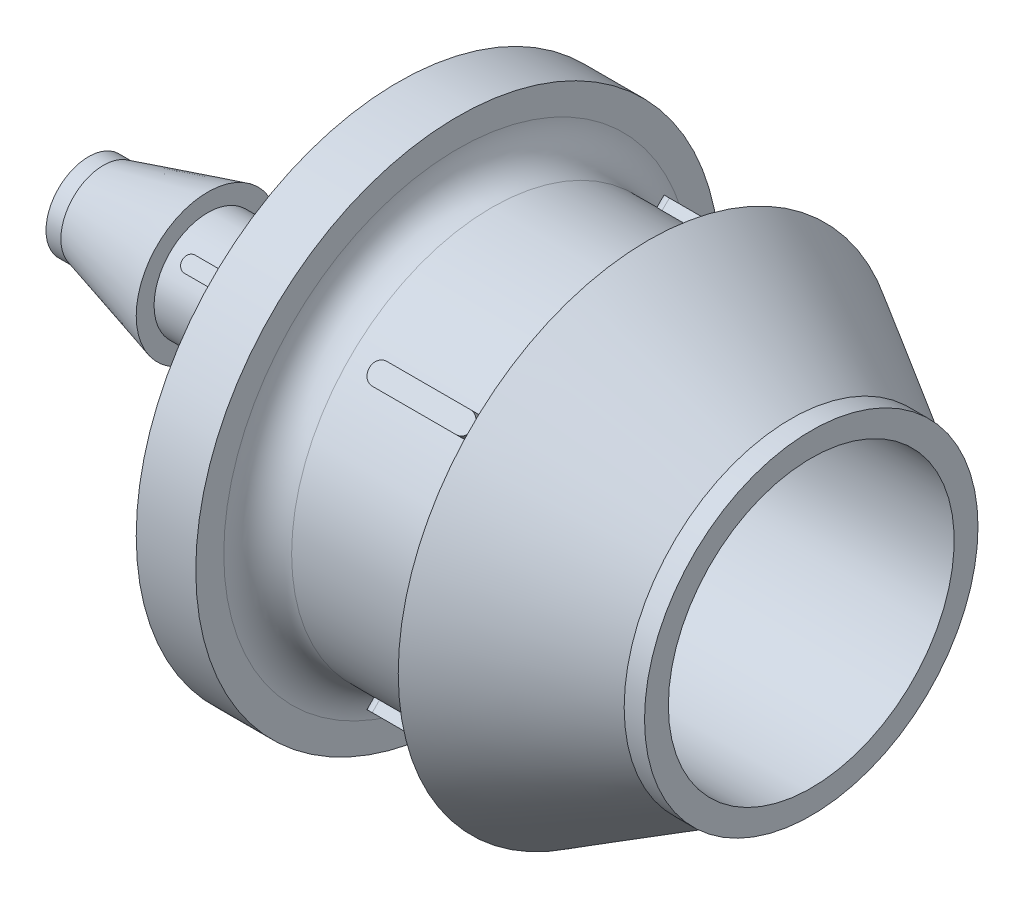
SolidWorks part; units mm, degrees
ref_plane "Front Plane" through (0, 0, 0) normal (0, 0, 1) x (1, 0, 0)
ref_plane "Top Plane" through (0, 0, 0) normal (0, 1, 0) x (1, 0, 0)
ref_plane "Right Plane" through (0, 0, 0) normal (1, 0, 0) x (0, 0, -1)
sketch "Sketch1" plane through (0, 0, 0) normal (0, 0, 1) x (1, 0, 0)
  line L0 (0, 0) -> (20.4343, 0) construction
  line L1 (20.4343, 7.62) -> (20.4343, 8.89)
  line L2 (-1.5875, 2.8575) -> (-1.5875, 13.97)
  line L3 (11.7475, 13.335) -> (11.7475, 10.668)
  line L4 (11.7475, 10.668) -> (1.5875, 10.668)
  line L5 (20.4343, 8.89) -> (19.3485, 8.89)
  line L6 (1.5875, 10.668) -> (1.5875, 13.97)
  line L7 (1.5875, 13.97) -> (-1.5875, 13.97)
  line L10 (20.4343, 7.62) -> (1.5875, 7.62)
  line L11 (0, 3.5451) -> (0, 7.62) construction
  line L12 (5.7328, 12.0015) -> (11.7475, 12.0015) construction
  line L13 (0, 0) -> (0, -4.0749) construction
  line L14 (19.3485, 8.89) -> (11.7475, 13.335)
  line L17 (-18.0975, 1.8161) -> (1.5875, 1.8161)
  line L18 (-18.0975, 1.8161) -> (-18.0975, 2.2701)
  line L19 (-18.0975, 2.2701) -> (-17.3038, 2.2701)
  line L20 (-17.3038, 2.2701) -> (-11.7475, 3.81)
  line L21 (-11.7475, 3.81) -> (-11.7475, 2.8575)
  line L22 (-11.7475, 2.8575) -> (-1.5875, 2.8575)
  line L23 (1.5875, 1.8161) -> (1.5875, 7.62)
  line L24 (-18.0975, 7.7522) -> (-18.0975, -1.9104) construction
  point P12 (0, 0)
  point P13 (1.5875, 5.969)
  point P16 (0, -4.0749)
  point P18 (0, 0)
  point P30 (1.5875, 1.8161)
  dimension "D1" = 17.78
  dimension "D3" = 8.6868
  dimension "D8" = 1.0858
  dimension "A1" = 3.6322
  dimension "B1" = 7.62
  dimension "D10" = 6.35
  dimension "D11" = 0.7937
  dimension "D12" = 4.5403
  dimension "D13" = 5.715
  dimension "D4" = 3.175
  dimension "D6" = 1.27
  dimension "D7" = 10.16
  dimension "D9" = 10.16
revolve "Revolve1" add sketch "Sketch1" angle 360 about L0
sketch "Sketch2" plane through (0, 0, 0) normal (0, 0, 1) x (1, 0, 0)
  line L0 (11.7475, 10.668) -> (1.5875, 10.668) construction
  line L1 (1.5875, 10.668) -> (1.5875, 13.97) construction
  line L2 (3.396, 10.668) -> (1.5875, 10.668)
  line L3 (1.5875, 10.668) -> (1.5875, 12.4765)
  line L9 (-11.7475, 2.8575) -> (-1.5875, 2.8575) construction
  line L10 (-1.5875, 2.8575) -> (-1.5875, 13.97) construction
  line L12 (-7.1438, 2.8575) -> (-1.5875, 2.8575)
  line L13 (-1.5875, 2.8575) -> (-1.5875, 8.4138)
  arc A0 (1.5875, 12.4765) -> (3.396, 10.668) centre (3.396, 12.4765) ccw
  arc A2 (-1.5875, 8.4138) -> (-7.1438, 2.8575) centre (-7.1438, 8.4138) cw
  dimension "D1" = 1.8085
revolve "Revolve2" add sketch "Sketch2" angle 360 about L0
ref_plane "Plane1" through (0, 0, 0) normal (0, 0.7071, 0.7071) x (-1, 0, 0)
sketch "Sketch3" plane through (0, 0, 0) normal (0, 0.7071, 0.7071) x (-1, 0, 0)
  line L0 (0, 0) -> (-20.4343, 0) construction
  line L1 (-5.3308, 0.5429) -> (-9.8127, 0.5429)
  line L2 (-5.3308, 0.5429) -> (-5.3308, -0.5429) construction
  line L3 (-5.3308, -0.5429) -> (-9.8127, -0.5429)
  line L4 (-9.8127, 0.5429) -> (-9.8127, -0.5429) construction
  line L5 (-4.7879, 3.344) -> (-4.7879, -2.3159) construction
  line L6 (-6.1798, 4.5434) -> (-8.9637, 4.5434) construction
  line L7 (-8.9637, 3.344) -> (-8.9637, 4.5434) construction
  line L8 (-7.5717, 4.5434) -> (-7.5717, 0.5429) construction
  line L9 (-3.396, 3.344) -> (-6.1798, 3.344) construction
  line L10 (7.1438, 3.2566) -> (8.6783, 3.2566) construction
  line L11 (-11.7475, 3.344) -> (-8.9637, 3.344) construction
  line L12 (8.6783, 3.2566) -> (8.6783, 4.0351) construction
  line L13 (-6.1798, 4.5434) -> (-6.1798, 3.344) construction
  line L14 (8.6783, 4.0351) -> (10.2129, 4.0351) construction
  line L15 (10.2129, 4.0351) -> (10.2129, 3.344) construction
  line L16 (10.2129, 3.344) -> (11.7475, 3.344) construction
  line L17 (9.4456, 4.0351) -> (9.4456, 0.3969) construction
  line L19 (8.3079, 0.3969) -> (10.5833, 0.3969) construction
  line L20 (8.3079, 0.3969) -> (8.3079, -0.3969) construction
  line L21 (8.3079, -0.3969) -> (10.5833, -0.3969) construction
  line L22 (10.5833, 0.3969) -> (10.5833, -0.3969) construction
  line L23 (7.911, 3.2566) -> (7.911, -1.2294) construction
  line L24 (0, 0) -> (24.6192, 0) construction
  arc A0 (-9.8127, 0.5429) -> (-9.8127, -0.5429) centre (-9.8127, 0) ccw
  arc A1 (-5.3308, 0.5429) -> (-5.3308, -0.5429) centre (-5.3308, 0) cw
  arc A2 (10.5833, 0.3969) -> (10.5833, -0.3969) centre (10.5833, 0) cw construction
  arc A3 (8.3079, 0.3969) -> (8.3079, -0.3969) centre (8.3079, 0) ccw construction
  dimension "D1" = 1.0858
  dimension "D2" = 0.7937
extrude "Extrude1" add sketch "Sketch3" along normal mid plane 22.4028
sketch "Sketch6" plane through (0, 0, 0) normal (0, 0.7071, 0.7071) x (-1, 0, 0)
  line L0 (8.3079, 0.3969) -> (10.5833, 0.3969) construction
  line L1 (8.3079, -0.3969) -> (10.5833, -0.3969) construction
  line L2 (8.3079, 0.3969) -> (10.5833, 0.3969)
  line L3 (8.3079, -0.3969) -> (10.5833, -0.3969)
  arc A0 (10.5833, -0.3969) -> (10.5833, 0.3969) centre (10.5833, 0) ccw construction
  arc A1 (8.3079, 0.3969) -> (8.3079, -0.3969) centre (8.3079, 0) ccw construction
  arc A2 (10.5833, -0.3969) -> (10.5833, 0.3969) centre (10.5833, 0) ccw
  arc A3 (8.3079, 0.3969) -> (8.3079, -0.3969) centre (8.3079, 0) ccw
extrude "Extrude2" add sketch "Sketch6" along normal mid plane 6.0007
pattern_circular "CirPattern1" count 2 every 90 about axis through (0, 0, 0) along (1, 0, 0) of "Extrude1", "Extrude2"
sketch "Sketch4" plane through (20.4343, 0, 0) normal (1, 0, 0) x (0, 0, -1)
  circle A0 centre (0, 0) radius 7.62 construction
  circle A1 centre (0, 0) radius 7.62
extrude "Cut-Extrude1" cut sketch "Sketch4" against normal up to vertex (20.4343 mm away) up to point (0, 7.62, 0)
sketch "Sketch7" plane through (-18.0975, 0, 0) normal (-1, 0, 0) x (0, 0, 1)
  circle A0 centre (0, 0) radius 1.8161 construction
  circle A1 centre (0, 0) radius 1.8161
extrude "Cut-Extrude2" cut sketch "Sketch7" against normal through all
equation "\"D2@Sketch1\" = \"B@Sketch1\"*.8"
equation "\"D8@Sketch1\" = \"D3@Sketch1\"/8"
equation "\"D1@Sketch3\" = \"D8@Sketch1\""
equation "\"D1@Extrude1\" = \"D2@Sketch1\"*1.05"
equation "\"D11@Sketch1\" = \"D10@Sketch1\"/8"
equation "\"D12@Sketch1\" = \"A1@Sketch1\"*1.25"
equation "\"D13@Sketch1\" = \"B1@Sketch1\"*.750"
equation "\"D2@Sketch3\" = \"D11@Sketch1\""
equation "\"D1@Extrude2\" = \"D13@Sketch1\"*1.05"
